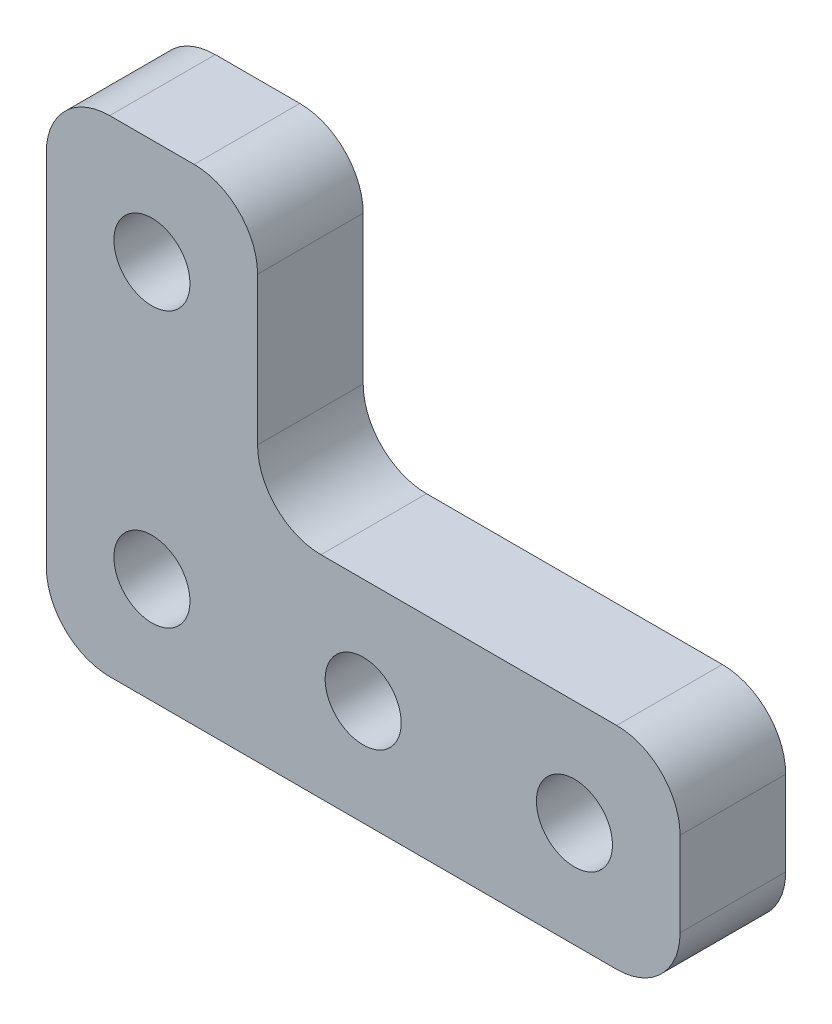
SolidWorks part; units mm, degrees
ref_plane "Front Plane" through (0, 0, 0) normal (0, 0, 1) x (1, 0, 0)
ref_plane "Top Plane" through (0, 0, 0) normal (0, 1, 0) x (1, 0, 0)
ref_plane "Right Plane" through (0, 0, 0) normal (1, 0, 0) x (0, 0, -1)
sketch "Sketch1" plane through (0, 0, 0) normal (0, 0, 1) x (1, 0, 0)
  line L0 (-6.35, -6.35) -> (-6.35, 22.86)
  line L1 (-6.35, 22.86) -> (6.35, 22.86)
  line L2 (6.35, 22.86) -> (6.35, 6.35)
  line L3 (6.35, 6.35) -> (31.75, 6.35)
  line L4 (31.75, 6.35) -> (31.75, -6.35)
  line L5 (31.75, -6.35) -> (-6.35, -6.35)
  circle A0 centre (0, 0) radius 2.286
  circle A1 centre (12.7, 0) radius 2.286
  circle A2 centre (25.4, 0) radius 2.286
  circle A5 centre (0, 16.51) radius 2.286
  point P3 (0, 0)
  point P4 (6.35, 21.59)
  point P5 (0, 0)
  dimension "D1" = 4.572
  dimension "D5" = 16.51
  dimension "D2" = 6.35
  dimension "D3" = 6.35
  dimension "D4" = 12.7
  dimension "D7" = 25.4
  dimension "D8" = 38.1
  dimension "D6" = 6.35
  dimension "D9" = 12.7
extrude "Boss-Extrude1" add sketch "Sketch1" along normal blind 6.35
fillet "Fillet1" radius 3.81 6 edges at (31.75, 6.35, 3.175) (31.75, -6.35, 3.175) (-6.35, -6.35, 3.175) (-6.35, 22.86, 3.175) (6.35, 22.86, 3.175) (6.35, 6.35, 3.175)
